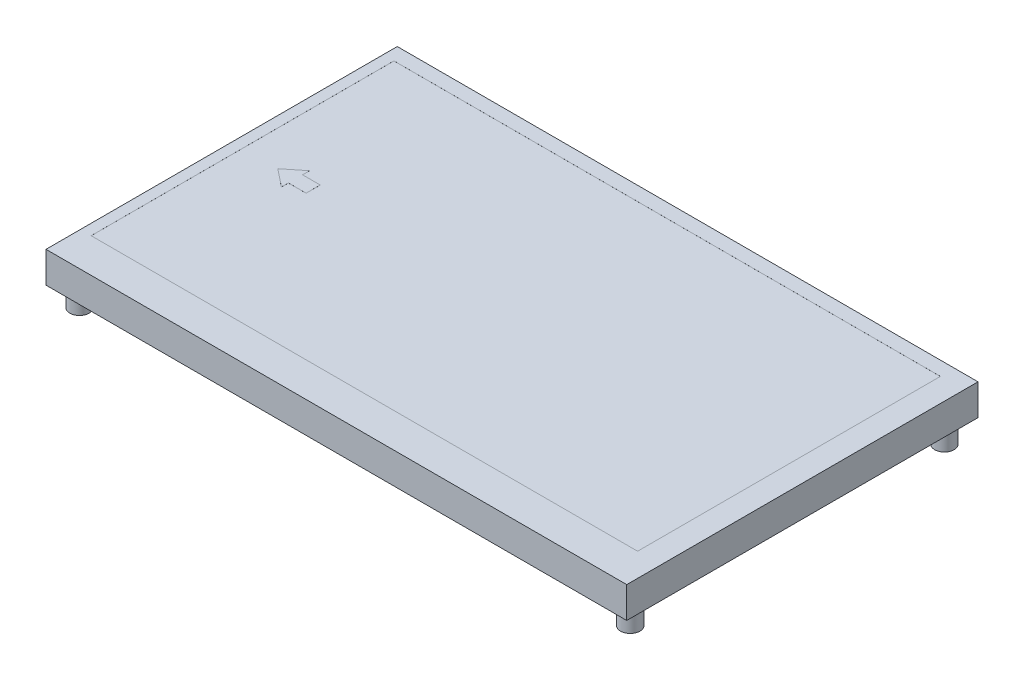
SolidWorks part; units mm, degrees
ref_plane "Front Plane" through (0, 0, 0) normal (0, 0, 1) x (1, 0, 0)
ref_plane "Top Plane" through (0, 0, 0) normal (0, 1, 0) x (1, 0, 0)
ref_plane "Right Plane" through (0, 0, 0) normal (1, 0, 0) x (0, 0, -1)
sketch "Sketch1" plane through (0, 0, 0) normal (0, 1, 0) x (1, 0, 0)
  line L1 (-82.25, 49.75) -> (82.25, 49.75)
  line L2 (-82.25, 49.75) -> (-82.25, -49.75)
  line L3 (-82.25, -49.75) -> (82.25, -49.75)
  line L4 (82.25, 49.75) -> (82.25, -49.75)
  line L5 (-82.25, 49.75) -> (82.25, -49.75) construction
  line L6 (-82.25, -49.75) -> (82.25, 49.75) construction
  point P0 (0, 0)
  dimension "D1" = 164.5
  dimension "D2" = 99.5
extrude "Boss-Extrude1" add sketch "Sketch1" along normal blind 8.8
sketch "Sketch2" plane through (0, 0, 0) normal (0, -1, 0) x (1, 0, 0)
  line L0 (0, 21.7771) -> (0, -10.6466) construction
  line L1 (-18.7928, 0) -> (14.2761, 0) construction
  circle A0 centre (-78, 44.5) radius 2.75
  circle A1 centre (78, 44.5) radius 2.75
  circle A2 centre (78, -44.5) radius 2.75
  circle A3 centre (-78, -44.5) radius 2.75
  circle A4 centre (-78, 44.5) radius 1.25
  circle A5 centre (78, 44.5) radius 1.25
  circle A6 centre (78, -44.5) radius 1.25
  circle A7 centre (-78, -44.5) radius 1.25
  dimension "D3" = 5.5
  dimension "D4" = 2.5
  dimension "D1" = 156
  dimension "D2" = 89
extrude "Boss-Extrude2" add sketch "Sketch2" along normal blind 6
sketch "Sketch3" plane through (0, 8.8, 0) normal (0, 1, 0) x (1, 0, 0)
  line L0 (82.25, -49.75) -> (82.25, 49.75) construction
  line L1 (-82.25, -49.75) -> (82.25, -49.75) construction
  line L2 (82.25, 49.75) -> (-82.25, 49.75) construction
  line L3 (-79.19, -40.02) -> (75.6, -40.02)
  line L4 (-79.19, -40.02) -> (-79.19, 45.75)
  line L5 (-79.19, 45.75) -> (75.6, 45.75)
  line L6 (75.6, -40.02) -> (75.6, 45.75)
  line L7 (-79.19, -40.02) -> (75.6, 45.75) construction
  line L8 (-79.19, 45.75) -> (75.6, -40.02) construction
  line L9 (-82.25, 49.75) -> (-82.25, -49.75) construction
  line L10 (-1.795, 45.75) -> (-1.795, -40.02) construction
  line L16 (-79.19, -40.02) -> (-79.19, 45.75)
  line L17 (75.6, -40.02) -> (75.6, 45.75)
  line L20 (-79.19, 2.865) -> (75.6, 2.865) construction
  line L21 (65.6, 2.865) -> (60.6, 6.865) construction
  line L22 (60.6, 6.865) -> (60.6, 4.865) construction
  line L23 (60.6, 4.865) -> (55.6, 4.865) construction
  line L24 (60.6, 0.865) -> (55.6, 0.865) construction
  line L25 (60.6, -1.135) -> (60.6, 0.865) construction
  line L26 (65.6, 2.865) -> (60.6, -1.135) construction
  line L27 (55.6, 4.865) -> (55.6, 0.865) construction
  line L28 (-64.19, -1.135) -> (-64.19, 0.865)
  line L29 (-69.19, 2.865) -> (-64.19, -1.135)
  line L30 (-69.19, 2.865) -> (-64.19, 6.865)
  line L31 (-64.19, 6.865) -> (-64.19, 4.865)
  line L32 (-64.19, 4.865) -> (-59.19, 4.865)
  line L33 (-59.19, 4.865) -> (-59.19, 0.865)
  line L34 (-64.19, 0.865) -> (-59.19, 0.865)
  point P4 (-1.795, 2.865)
  dimension "D1" = 4
  dimension "D2" = 3.06
  dimension "D3" = 6.65
  dimension "D4" = 9.73
  dimension "D10" = 5
  dimension "D11" = 4
  dimension "D12" = 5
  dimension "D13" = 8
  dimension "D14" = 10
extrude "Cut-Extrude1" cut sketch "Sketch3" against normal blind 0.01
sketch "Sketch4" plane through (-82.25, 0, 0) normal (-1, 0, 0) x (0, 0, 1)
  line L0 (31.85, -1.51) -> (37.75, -1.51) construction
  line L1 (31.85, -0.01) -> (37.75, -0.01)
  line L2 (31.85, -3.01) -> (37.75, -3.01)
  line L3 (49.75, 8.8) -> (49.75, 0) construction
  line L5 (31.85, -0.16) -> (37.75, -0.16)
  line L6 (31.85, -2.86) -> (37.75, -2.86)
  line L7 (-49.75, 0) -> (49.75, 0) construction
  arc A0 (31.85, -0.01) -> (31.85, -3.01) centre (31.85, -1.51) ccw
  arc A1 (37.75, -3.01) -> (37.75, -0.01) centre (37.75, -1.51) ccw
  arc A2 (37.75, -2.86) -> (37.75, -0.16) centre (37.75, -1.51) ccw
  arc A3 (31.85, -0.16) -> (31.85, -2.86) centre (31.85, -1.51) ccw
  point P2 (34.8, -1.51)
  point P7 (30.35, -1.51)
  point P8 (39.25, -1.51)
  dimension "D1" = 8.9
  dimension "D2" = 3
  dimension "D3" = 10.5
  dimension "D5" = 0.01
  dimension "D4" = 0.15
extrude "Boss-Extrude3" add sketch "Sketch4" against normal blind 7.3
sketch "Sketch5" plane through (0, 0, 0) normal (0, -1, 0) x (1, 0, 0)
  line L0 (-80.75, 44.5) -> (-75.25, 44.5) construction
  line L1 (-69.9, 47.5) -> (-66.1, 47.5)
  line L2 (-69.9, 47.5) -> (-69.9, 44.5)
  line L3 (-69.9, 44.5) -> (-66.1, 44.5)
  line L4 (-66.1, 47.5) -> (-66.1, 44.5)
  line L5 (-69.9, 47.5) -> (-66.1, 44.5) construction
  line L6 (-69.9, 44.5) -> (-66.1, 47.5) construction
  line L11 (0, 49.75) -> (0, -49.75) construction
  line L12 (-82.25, 49.75) -> (82.25, 49.75) construction
  line L13 (82.25, -49.75) -> (-82.25, -49.75) construction
  line L14 (69.9, 47.5) -> (66.1, 47.5)
  line L15 (69.9, 47.5) -> (69.9, 44.5)
  line L16 (69.9, 44.5) -> (66.1, 44.5)
  line L17 (66.1, 47.5) -> (66.1, 44.5)
  circle A0 centre (-78, 44.5) radius 2.75 construction
  circle A1 centre (-78, 44.5) radius 2.75 construction
  point P0 (-68, 46)
  dimension "D1" = 3.8
  dimension "D2" = 3
  dimension "D3" = 10
extrude "Boss-Extrude4" add sketch "Sketch5" along normal blind 1.2
